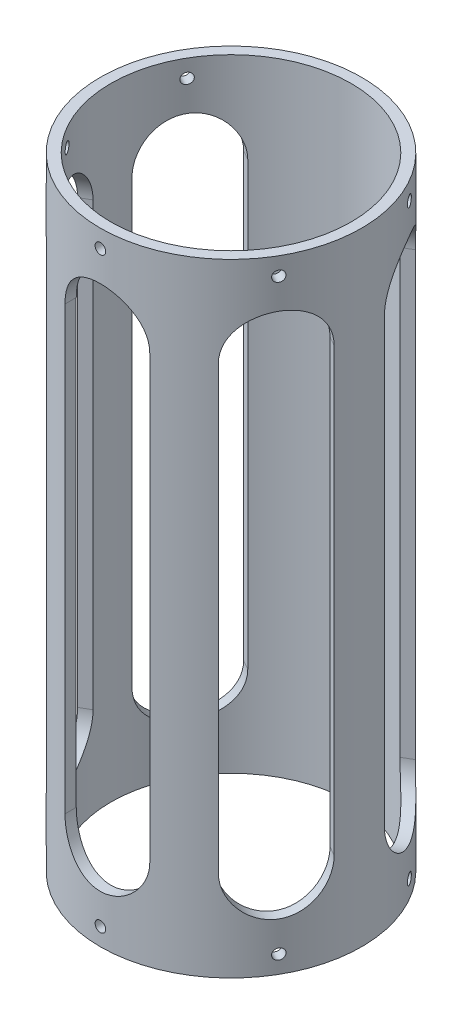
SolidWorks part; units mm, degrees
ref_plane "Front Plane" through (0, 0, 0) normal (0, 0, 1) x (1, 0, 0)
ref_plane "Top Plane" through (0, 0, 0) normal (0, 1, 0) x (1, 0, 0)
ref_plane "Right Plane" through (0, 0, 0) normal (1, 0, 0) x (0, 0, -1)
sketch "Sketch1" plane through (0, 0, 0) normal (0, 1, 0) x (1, 0, 0)
  circle A0 centre (0, 0) radius 34
  circle A1 centre (0, 0) radius 37
  dimension "D1" = 68
  dimension "D2" = 3
extrude "TUBE BASE EXTRUDE" add sketch "Sketch1" along normal blind 176.2
sketch "Sketch2" plane through (0, 0, 0) normal (0, 0, 1) x (1, 0, 0)
  line L0 (0, 25.6) -> (0, 150.6) construction
  line L1 (-12, 25.6) -> (-12, 150.6)
  line L2 (12, 25.6) -> (12, 150.6)
  circle A0 centre (0, 5) radius 1.5
  circle A1 centre (0, 171.2) radius 1.5
  arc A2 (-12, 25.6) -> (12, 25.6) centre (0, 25.6) ccw
  arc A3 (12, 150.6) -> (-12, 150.6) centre (0, 150.6) ccw
  point P6 (0, 88.1)
  dimension "D1" = 3
  dimension "D6" = 12
  dimension "D2" = 166.2
  dimension "D3" = 5
  dimension "D4" = 88.1
  dimension "D5" = 125
extrude "WEIGHT RELIEF AND SCREW HOLE" cut sketch "Sketch2" along normal through all
sketch "AXIS" plane through (0, 0, 0) normal (0, 0, 1) x (1, 0, 0)
  line L0 (0, 0) -> (0, 176.2)
  line L1 (-37, 0) -> (37, 0) construction
  line L2 (37, 176.2) -> (-37, 176.2) construction
pattern_circular "CirPattern1" count 3 every 60 about axis through (0, 0, 0) along (0, 1, 0) of "WEIGHT RELIEF AND SCREW HOLE"
pattern_circular "CirPattern2" count 3 every 60 about axis through (0, 0, 0) along (0, 1, 0) of "WEIGHT RELIEF AND SCREW HOLE"
